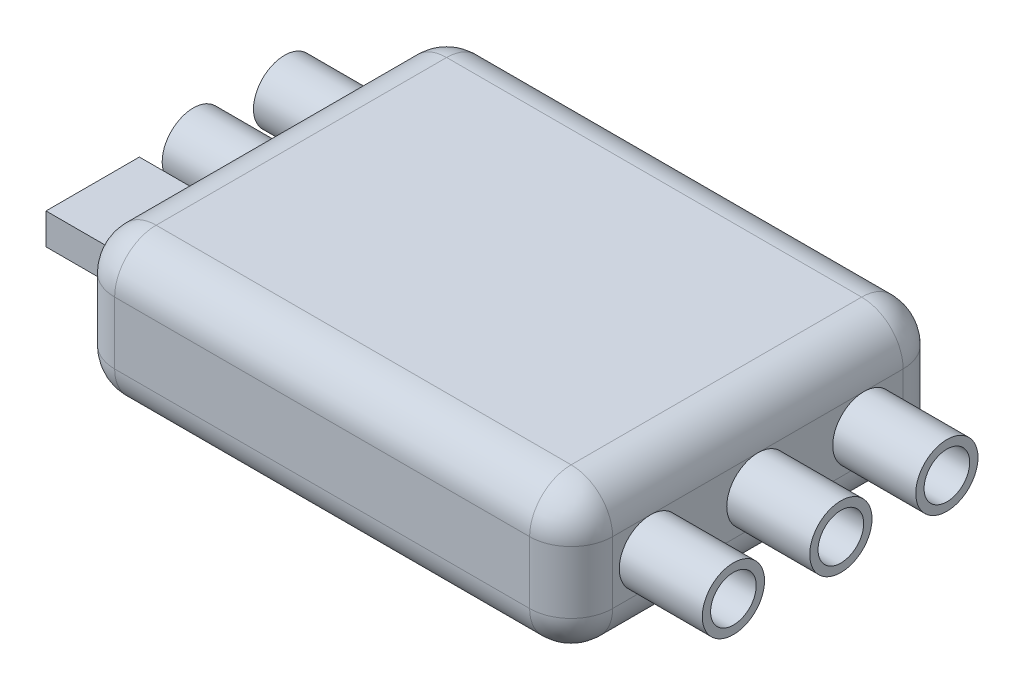
SolidWorks part; units mm, degrees
ref_plane "Front Plane" through (0, 0, 0) normal (0, 0, 1) x (1, 0, 0)
ref_plane "Top Plane" through (0, 0, 0) normal (0, 1, 0) x (1, 0, 0)
ref_plane "Right Plane" through (0, 0, 0) normal (1, 0, 0) x (0, 0, -1)
sketch "Sketch1" plane through (0, 0, 0) normal (0, 1, 0) x (1, 0, 0)
  line L1 (-10, 9) -> (10, 9)
  line L2 (-12, 7) -> (-12, -7)
  line L3 (-10, -9) -> (10, -9)
  line L4 (12, 7) -> (12, -7)
  line L5 (-12, 9) -> (12, -9) construction
  line L6 (-12, -9) -> (12, 9) construction
  arc A0 (-12, -7) -> (-10, -9) centre (-10, -7) ccw
  arc A1 (10, -9) -> (12, -7) centre (10, -7) ccw
  arc A2 (10, 9) -> (12, 7) centre (10, 7) cw
  arc A3 (-10, 9) -> (-12, 7) centre (-10, 7) ccw
  point P0 (0, 0)
  dimension "D3" = 2
  dimension "D1" = 24
  dimension "D2" = 18
extrude "Boss-Extrude1" add sketch "Sketch1" along normal blind 7
fillet "Fillet1" radius 2 16 edges at (0, 0, 9) (11.4142, 0, 8.4142) (12, 0, 0) (11.4142, 0, -8.4142) (0, 0, -9) (-11.4142, 0, -8.4142) (-12, 0, 0) (-11.4142, 0, 8.4142) (-12, 7, 0) (-11.4142, 7, -8.4142) (0, 7, -9) (11.4142, 7, -8.4142) (12, 7, 0) (11.4142, 7, 8.4142) (0, 7, 9) (-11.4142, 7, 8.4142)
sketch "Sketch2" plane through (12, 0, 0) normal (1, 0, 0) x (0, 0, -1)
  line L0 (-7, 3.5) -> (7, 3.5) construction
  line L1 (-7, 5) -> (-7, 2) construction
  line L2 (7, 5) -> (7, 2) construction
  circle A0 centre (0, 3.5) radius 1.1
  circle A1 centre (0, 3.5) radius 1.5
  circle A2 centre (-5.1791, 3.5) radius 1.5
  circle A3 centre (-5.1791, 3.5) radius 1.1
  circle A4 centre (5.1091, 3.5) radius 1.5
  circle A5 centre (5.1091, 3.5) radius 1.1
  dimension "D1" = 3
  dimension "D2" = 0.4
extrude "Boss-Extrude2" add sketch "Sketch2" along normal blind 4
sketch "Sketch3" plane through (-12, 0, 0) normal (-1, 0, 0) x (0, 0, 1)
  line L0 (-7, 3.5) -> (7, 3.5) construction
  line L1 (-7, 5) -> (-7, 2) construction
  line L2 (7, 5) -> (7, 2) construction
  line L4 (6.308, 4.25) -> (1.808, 4.25)
  line L5 (6.308, 4.25) -> (6.308, 2.75)
  line L6 (6.308, 2.75) -> (1.808, 2.75)
  line L7 (1.808, 4.25) -> (1.808, 2.75)
  circle A0 centre (-5.1908, 3.5) radius 1.5
  circle A1 centre (-0.7908, 3.5) radius 1.5
  circle A2 centre (-0.7908, 3.5) radius 1.1
  circle A3 centre (-5.1908, 3.5) radius 1.1
  dimension "D3" = 3
  dimension "D4" = 0.4
  dimension "D1" = 4.5
  dimension "D2" = 1.5
  dimension "D5" = 4.4
extrude "Boss-Extrude3" add sketch "Sketch3" along normal blind 4
